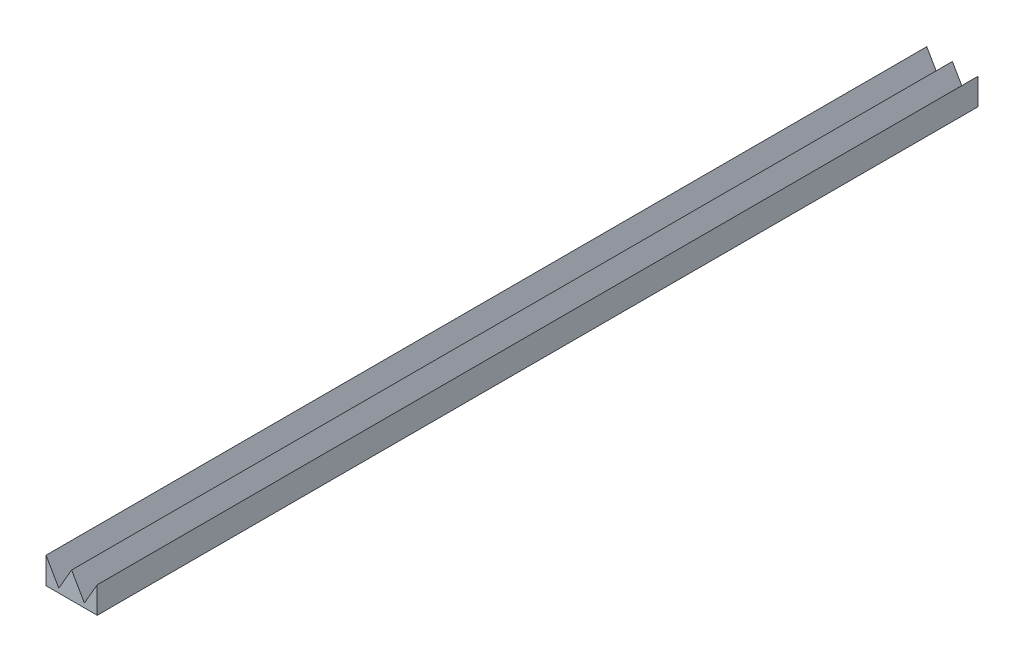
SolidWorks part; units mm, degrees
ref_plane "Front Plane" through (0, 0, 0) normal (0, 0, 1) x (1, 0, 0)
ref_plane "Top Plane" through (0, 0, 0) normal (0, 1, 0) x (1, 0, 0)
ref_plane "Right Plane" through (0, 0, 0) normal (1, 0, 0) x (0, 0, -1)
sketch "Sketch1" plane through (0, 0, 0) normal (0, 0, 1) x (1, 0, 0)
  line L0 (0, 0) -> (0, 5.1651)
  line L1 (0, 5.1651) -> (2.5, 0.8349)
  line L2 (2.5, 0.8349) -> (5, 5.1651)
  line L3 (5, 5.1651) -> (7.5, 0.8349)
  line L4 (7.5, 0.8349) -> (10, 5.1651)
  line L9 (10, 5.1651) -> (10, 0)
  line L10 (10, 0) -> (0, 0)
  line L11 (0, 5.1651) -> (5, 5.1651) construction
  dimension "D1" = 5
  dimension "D2" = 0.8349
extrude "Boss-Extrude1" add sketch "Sketch1" along normal blind 172
